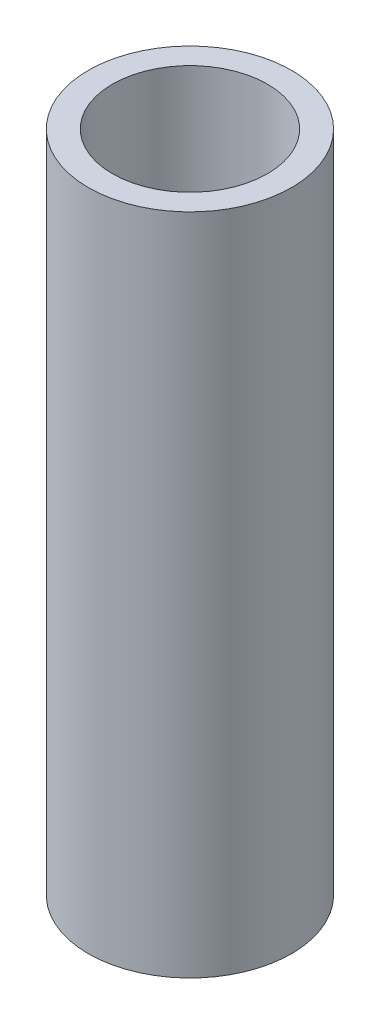
SolidWorks part; units mm, degrees
material "ABS"
ref_plane "Front Plane" through (0, 0, 0) normal (0, 0, 1) x (1, 0, 0)
ref_plane "Top Plane" through (0, 0, 0) normal (0, 1, 0) x (1, 0, 0)
ref_plane "Right Plane" through (0, 0, 0) normal (1, 0, 0) x (0, 0, -1)
sketch "Sketch1" plane through (0, 0, 0) normal (0, 1, 0) x (1, 0, 0)
  circle A0 centre (0, 0) radius 2.667
  circle A1 centre (0, 0) radius 3.4925
  dimension "D1" = 5.334
  dimension "D2" = 6.985
extrude "Boss-Extrude1" add sketch "Sketch1" along normal blind 22.8092
